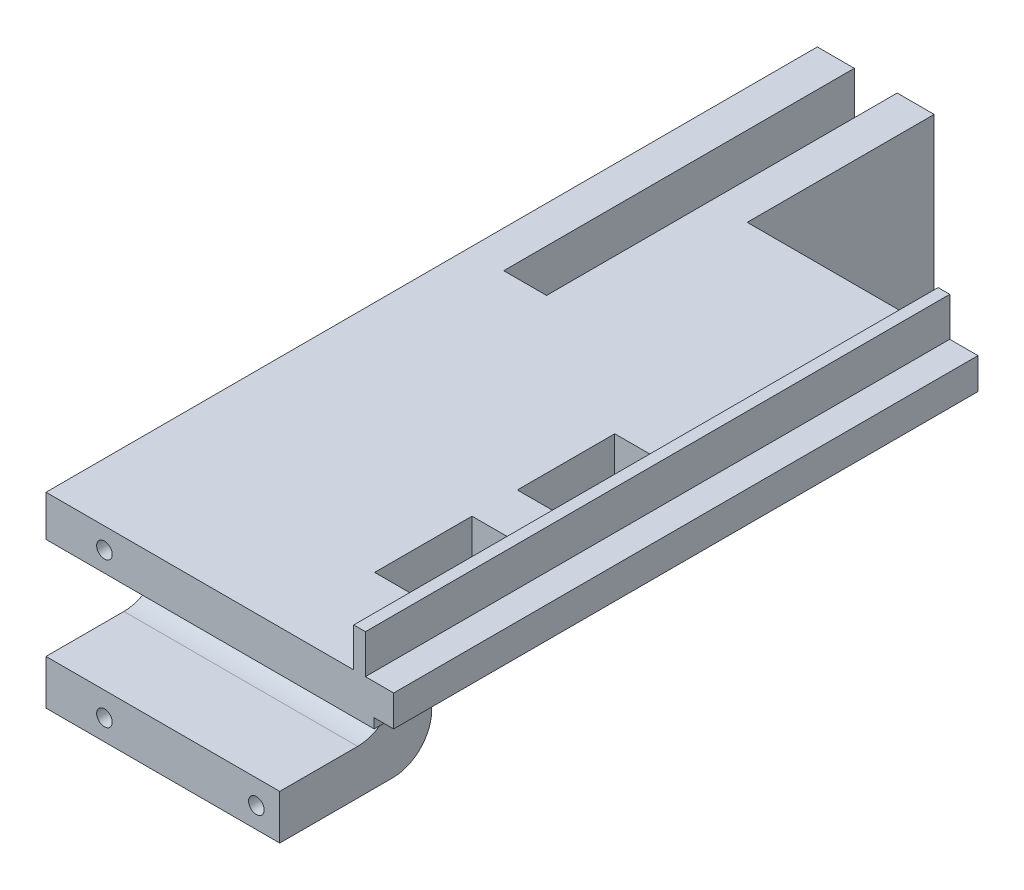
SolidWorks part; units mm, degrees
ref_plane "Alzado" through (0, 0, 0) normal (0, 0, 1) x (1, 0, 0)
ref_plane "Planta" through (0, 0, 0) normal (0, 1, 0) x (1, 0, 0)
ref_plane "Vista lateral" through (0, 0, 0) normal (1, 0, 0) x (0, 0, -1)
sketch "Croquis1" plane through (0, 0, 0) normal (0, 0, 1) x (1, 0, 0)
  line L1 (-66.2162, 31.0113) -> (-6.2162, 31.0113)
  line L2 (-66.2162, 31.0113) -> (-66.2162, -16.9887)
  line L3 (-66.2162, -16.9887) -> (-6.2162, -16.9887)
  line L4 (-6.2162, 31.0113) -> (-6.2162, -16.9887)
  dimension "D1" = 48
  dimension "D2" = 60
extrude "Saliente-Extruir1" add sketch "Croquis1" along normal blind 6
sketch "Croquis4" plane through (0, 0, 6) normal (0, 0, 1) x (1, 0, 0)
  line L0 (-66.2162, 31.0113) -> (-66.2162, 19.5113)
  line L1 (-66.2162, 31.0113) -> (-66.2162, -16.9887) construction
  line L3 (-66.2162, -5.4887) -> (-66.2162, -16.9887)
  line L4 (-66.2162, 31.0113) -> (-6.2162, 31.0113)
  line L6 (-6.2162, 31.0113) -> (-6.2162, 19.5113)
  line L7 (-6.2162, -16.9887) -> (-6.2162, 31.0113) construction
  line L8 (-6.2162, 19.5113) -> (-66.2162, 19.5113)
  line L9 (-66.2162, -5.4887) -> (-6.2162, -5.4887)
  line L10 (-6.2162, -5.4887) -> (-6.2162, -16.9887)
  line L11 (-6.2162, -16.9887) -> (-66.2162, -16.9887)
  dimension "D1" = 25
extrude "Saliente-Extruir3" add sketch "Croquis4" along normal blind 30
sketch "Croquis3" plane through (0, 0, 6) normal (0, 0, 1) x (1, 0, 0)
  circle A0 centre (-51.2162, 25.6613) radius 2.125
  circle A1 centre (-12.2162, 25.6613) radius 2.125
  circle A2 centre (-12.2162, -11.6387) radius 2.125
  circle A3 centre (-51.2162, -11.6387) radius 2.125
  dimension "D7" = 4.25
  dimension "D9" = 4.25
  dimension "D10" = 4.25
  dimension "D2" = 4.25
  dimension "D3" = 37.3
  dimension "D4" = 39
sketch "Croquis5" plane through (0, 0, 36) normal (0, 0, 1) x (1, 0, 0)
  circle A0 centre (-51.2162, 25.6613) radius 2
  circle A1 centre (-12.2162, 25.6613) radius 2
  circle A2 centre (-12.2162, -11.6387) radius 2
  circle A3 centre (-51.2162, -11.6387) radius 2
  dimension "D1" = 4
  dimension "D2" = 4
  dimension "D3" = 4
  dimension "D4" = 4
extrude "Cortar-Extruir3" cut sketch "Croquis5" against normal blind 16
sketch "Croquis6" plane through (0, 0, 0) normal (0, 0, -1) x (-1, 0, 0)
  line L0 (66.2162, -16.9887) -> (6.2162, -16.9887) construction
  line L1 (66.2162, 31.0113) -> (36.2162, 31.0113)
  line L2 (66.2162, 31.0113) -> (66.2162, -16.9887)
  line L3 (66.2162, -16.9887) -> (36.2162, -16.9887)
  line L4 (36.2162, 31.0113) -> (36.2162, -16.9887)
  dimension "D1" = 30
extrude "Saliente-Extruir4" add sketch "Croquis6" along normal blind 162
sketch "Croquis7" plane through (0, 0, -162) normal (0, 0, -1) x (-1, 0, 0)
  circle A0 centre (51.2162, 7.0113) radius 2
  dimension "D1" = 4
extrude "Cortar-Extruir4" cut sketch "Croquis7" against normal blind 16
sketch "Croquis8" plane through (0, 0, -162) normal (0, 0, -1) x (-1, 0, 0)
  line L0 (41.2162, 12.0113) -> (41.2162, 9.5131)
  line L10 (36.2162, 12.0113) -> (41.2162, 12.0113)
  line L11 (36.2162, 12.0113) -> (36.2162, 2.0113)
  line L12 (36.2162, 2.0113) -> (41.2162, 2.0113)
  line L21 (41.2162, 9.5131) -> (44.2162, 9.5131)
  line L23 (41.2162, 4.5131) -> (44.2162, 4.5131)
  line L24 (44.2162, 9.5131) -> (44.2162, 4.5131)
  line L25 (41.2162, 2.0113) -> (41.2162, 4.5131)
  dimension "D1" = 5
  dimension "D2" = 3
  dimension "D3" = 5
sketch "Croquis11" plane through (-36.2162, 0, 0) normal (1, 0, 0) x (0, 0, -1)
  line L1 (-36, 19.5113) -> (-36, 31.0113) construction
  line L4 (-36, 19.5113) -> (-36, 31.0113)
  line L6 (-36, 19.5113) -> (114, 19.5113)
  line L7 (114, 19.5113) -> (114, 31.0113)
  line L8 (162, 31.0113) -> (0, 31.0113) construction
  line L9 (162, 31.0113) -> (0, 31.0113) construction
  line L10 (-36, 31.0113) -> (114, 31.0113)
  dimension "D1" = 150
extrude "Saliente-Extruir6" add sketch "Croquis11" along normal blind 59.25
sketch "Croquis12" plane through (0, 31.0113, 0) normal (0, 1, 0) x (1, 0, 0)
  line L0 (23.0338, -36) -> (-66.2162, -36) construction
  line L1 (15.7838, -36) -> (12.7838, -36)
  line L2 (-66.2162, -36) -> (-66.2162, 162) construction
  line L3 (-66.2162, -36) -> (-66.2162, 162) construction
  line L4 (15.7838, -36) -> (15.7838, 114)
  line L5 (15.7838, 114) -> (12.7838, 114)
  line L6 (23.0338, 114) -> (-36.2162, 114) construction
  line L7 (12.7838, 114) -> (12.7838, -36)
  dimension "D1" = 82
  dimension "D2" = 150
  dimension "D3" = 3
extrude "Saliente-Extruir7" add sketch "Croquis12" along normal blind 10
sketch "Croquis14" plane through (0, 0, -114) normal (0, 0, -1) x (-1, 0, 0)
  line L0 (-23.0338, 23.0113) -> (-18.0338, 23.0113)
  line L1 (-18.0338, 23.0113) -> (-18.0338, 19.5113)
  line L2 (-23.0338, 23.0113) -> (-23.0338, 19.5113)
  line L3 (-23.0338, 19.5113) -> (-18.0338, 19.5113)
  line L4 (36.2162, 19.5113) -> (36.2162, 31.0113)
  line L5 (36.2162, 31.0113) -> (-12.7838, 31.0113)
  line L6 (-23.0338, 31.0113) -> (-23.0338, 19.5113)
  line L7 (-23.0338, 19.5113) -> (36.2162, 19.5113)
  line L8 (36.2162, 19.5113) -> (36.2162, 31.0113) construction
  line L9 (36.2162, 31.0113) -> (-12.7838, 31.0113) construction
  line L10 (-23.0338, 31.0113) -> (-23.0338, 19.5113) construction
  line L11 (-23.0338, 19.5113) -> (36.2162, 19.5113) construction
  line L20 (-12.7838, 31.0113) -> (-12.7838, 41.0113)
  line L22 (-12.7838, 41.0113) -> (-15.7838, 41.0113)
  line L24 (-15.7838, 41.0113) -> (-15.7838, 31.0113)
  line L26 (-15.7838, 31.0113) -> (-23.0338, 31.0113)
  line L27 (-15.7838, 31.0113) -> (-23.0338, 31.0113) construction
  dimension "D2" = 5
  dimension "D3" = 8
  dimension "D1" = 0
extrude "Cortar-Extruir6" cut sketch "Croquis14" against normal through all both and the other way through all
sketch "Croquis15" plane through (0, 0, -162) normal (0, 0, -1) x (-1, 0, 0)
  line L0 (51.2162, 45.0729) -> (51.2162, 16.9496) construction
  line L1 (56.7162, 20.0113) -> (45.7162, 20.0113)
  line L2 (45.7162, 20.0113) -> (45.7162, 31.0113)
  line L3 (56.7162, 20.0113) -> (56.7162, 31.0113)
  line L4 (66.2162, -16.9887) -> (66.2162, 31.0113)
  line L5 (66.2162, 31.0113) -> (36.2162, 31.0113)
  line L6 (36.2162, 31.0113) -> (36.2162, -16.9887)
  line L7 (36.2162, -16.9887) -> (66.2162, -16.9887)
  line L8 (66.2162, -16.9887) -> (66.2162, 31.0113) construction
  line L9 (66.2162, 31.0113) -> (36.2162, 31.0113) construction
  line L10 (56.7162, 31.0113) -> (45.7162, 31.0113)
  point P6 (51.2162, 31.0113)
  point P10 (51.2162, 20.0113)
  dimension "D2" = 11
  dimension "D3" = 11
  dimension "D1" = 0
extrude "Cortar-Extruir7" cut sketch "Croquis15" against normal blind 90 and the other way through all
sketch "Croquis16" plane through (-66.2162, 0, 0) normal (-1, 0, 0) x (0, 0, 1)
  line L0 (6, 19.5113) -> (6, 20.5113)
  line L1 (6, 20.5113) -> (36, 20.5113)
  line L2 (36, 31.0113) -> (36, 19.5113) construction
  line L3 (6, 19.5113) -> (36, 19.5113)
  line L4 (36, 19.5113) -> (36, 20.5113)
  dimension "D1" = 1
extrude "Cortar-Extruir10" cut sketch "Croquis16" against normal through all contours L1 L4 L3 L0
fillet "Redondeo1" radius 10 2 edges at (-36.2162, -5.4887, 6) (-24.0912, 20.5113, 6)
sketch "Croquis20" plane through (0, 0, 0) normal (0, 0, -1) x (-1, 0, 0)
  line L1 (6.2162, 19.5113) -> (36.2162, 19.5113)
  line L2 (6.2162, 19.5113) -> (6.2162, -16.9887)
  line L3 (6.2162, -16.9887) -> (36.2162, -16.9887)
  line L4 (36.2162, 19.5113) -> (36.2162, -16.9887)
extrude "Saliente-Extruir8" add sketch "Croquis20" along normal blind 50
sketch "Croquis21" plane through (0, 19.5113, 0) normal (0, -1, 0) x (1, 0, 0)
  line L1 (5.7838, 11.6411) -> (-6.2162, 11.6411)
  line L2 (5.7838, 11.6411) -> (5.7838, -13.3589)
  line L3 (5.7838, -13.3589) -> (-6.2162, -13.3589)
  line L4 (-6.2162, 11.6411) -> (-6.2162, -13.3589)
  line L5 (18.0338, 11.6411) -> (-6.2162, 11.6411) construction
  line L6 (-6.2162, 36) -> (-6.2162, -50) construction
  line L8 (-6.2162, -50) -> (5.7838, -50)
  line L9 (-6.2162, -50) -> (-6.2162, -25)
  line L10 (-6.2162, -25) -> (5.7838, -25)
  line L11 (5.7838, -50) -> (5.7838, -25)
  dimension "D1" = 12
  dimension "D2" = 25
  dimension "D3" = 25
extrude "Cortar-Extruir11" cut sketch "Croquis21" against normal blind 40
sketch "Croquis22" plane through (0, 0, -50) normal (0, 0, -1) x (-1, 0, 0)
  line L1 (36.2162, 19.5113) -> (6.2162, 19.5113)
  line L2 (36.2162, 19.5113) -> (36.2162, -16.9887)
  line L3 (36.2162, -16.9887) -> (6.2162, -16.9887)
  line L4 (6.2162, 19.5113) -> (6.2162, -16.9887)
extrude "Cortar-Extruir13" cut sketch "Croquis22" against normal blind 47
fillet "Redondeo3" radius 10 1 edges at (-21.2162, -16.9887, -3)
